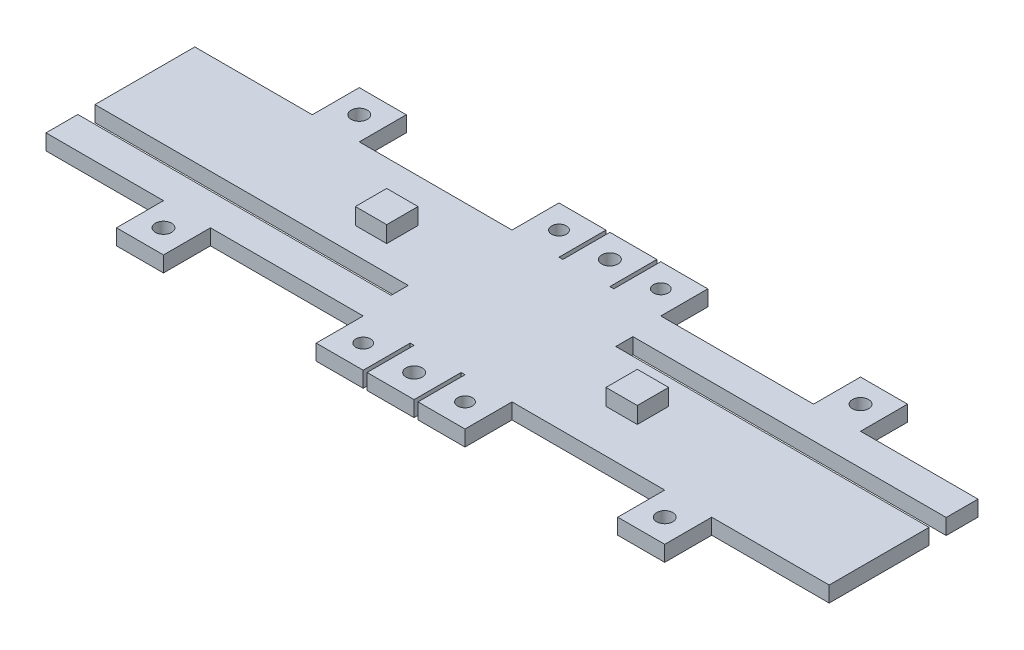
SolidWorks part; units mm, degrees
ref_plane "Front Plane" through (0, 0, 0) normal (0, 0, 1) x (1, 0, 0)
ref_plane "Top Plane" through (0, 0, 0) normal (0, 1, 0) x (1, 0, 0)
ref_plane "Right Plane" through (0, 0, 0) normal (1, 0, 0) x (0, 0, -1)
sketch "Sketch1" plane through (0, 0, 0) normal (0, 1, 0) x (1, 0, 0)
  line L1 (0, 0) -> (160, 0)
  line L2 (0, 0) -> (0, -30.4)
  line L3 (0, -30.4) -> (160, -30.4)
  line L4 (160, 0) -> (160, -30.4)
  dimension "D1" = 30.4
  dimension "D2" = 160
extrude "Boss-Extrude1" add sketch "Sketch1" along normal blind 3.2
sketch "Sketch2" plane through (0, 3.2, 0) normal (0, 1, 0) x (1, 0, 0)
  line L0 (0, -30.4) -> (160, -30.4) construction
  line L1 (24, -30.4) -> (33.6, -30.4)
  line L2 (24, -30.4) -> (24, -40)
  line L3 (24, -40) -> (33.6, -40)
  line L4 (33.6, -30.4) -> (33.6, -40)
  line L5 (75.2, -30.4) -> (75.2, -40)
  line L6 (75.2, -40) -> (84.8, -40)
  line L7 (75.2, -30.4) -> (84.8, -30.4)
  line L8 (84.8, -30.4) -> (84.8, -40)
  line L9 (126.4, -30.4) -> (126.4, -40)
  line L10 (126.4, -40) -> (136, -40)
  line L11 (126.4, -30.4) -> (136, -30.4)
  line L12 (136, -30.4) -> (136, -40)
  line L13 (75.2, 9.6) -> (75.2, 0)
  line L14 (75.2, 0) -> (84.8, 0)
  line L15 (75.2, 9.6) -> (84.8, 9.6)
  line L16 (84.8, 9.6) -> (84.8, 0)
  line L17 (126.4, 9.6) -> (126.4, 0)
  line L18 (126.4, 0) -> (136, 0)
  line L19 (126.4, 9.6) -> (136, 9.6)
  line L20 (136, 9.6) -> (136, 0)
  line L21 (24, 9.6) -> (24, 0)
  line L22 (24, 0) -> (33.6, 0)
  line L23 (24, 9.6) -> (33.6, 9.6)
  line L24 (33.6, 9.6) -> (33.6, 0)
  circle A0 centre (28.8, -35.2) radius 1.65
  circle A1 centre (80, -35.2) radius 1.65
  circle A2 centre (131.2, -35.2) radius 1.65
  circle A3 centre (80, 4.8) radius 1.65
  circle A4 centre (131.2, 4.8) radius 1.65
  circle A5 centre (28.8, 4.8) radius 1.65
  dimension "D5" = 3.3
  dimension "D1" = 9.6
  dimension "D2" = 9.6
  dimension "D3" = 24
  dimension "D6" = 3
  dimension "D4" = 2
extrude "Boss-Extrude2" add sketch "Sketch2" against normal blind 3.2
sketch "Sketch3" plane through (0, 3.2, 0) normal (0, 1, 0) x (1, 0, 0)
  line L0 (0, 0) -> (0, -30.4) construction
  line L1 (0, -20.4) -> (64, -20.4)
  line L2 (0, -20.4) -> (0, -23.9)
  line L3 (0, -23.9) -> (64, -23.9)
  line L4 (64, -20.4) -> (64, -23.9)
  line L5 (160, -30.4) -> (160, 0) construction
  line L6 (160, -6.5) -> (96, -6.5)
  line L7 (160, -6.5) -> (160, -10)
  line L8 (160, -10) -> (96, -10)
  line L9 (96, -6.5) -> (96, -10)
  dimension "D1" = 10.4
  dimension "D2" = 3.5
  dimension "D3" = 3.5
  dimension "D4" = 64
  dimension "D5" = 64
  dimension "D6" = 6.5
extrude "Cut-Extrude1" cut sketch "Sketch3" against normal through all
sketch "Sketch4" plane through (0, 3.2, 0) normal (0, 1, 0) x (1, 0, 0)
  line L0 (33.6, -30.4) -> (75.2, -30.4) construction
  line L1 (64.8, -30.4) -> (74.4, -30.4)
  line L2 (64.8, -30.4) -> (64.8, -40)
  line L3 (64.8, -40) -> (74.4, -40)
  line L4 (74.4, -30.4) -> (74.4, -40)
  line L5 (84.8, -30.4) -> (126.4, -30.4) construction
  line L6 (85.6, -30.4) -> (95.2, -30.4)
  line L7 (85.6, -30.4) -> (85.6, -40)
  line L8 (85.6, -40) -> (95.2, -40)
  line L9 (95.2, -30.4) -> (95.2, -40)
  line L10 (160, -15.2) -> (144.3037, -15.2) construction
  line L11 (160, -30.4) -> (160, -10) construction
  line L12 (85.6, 9.6) -> (95.2, 9.6)
  line L13 (95.2, 0) -> (95.2, 9.6)
  line L14 (85.6, 0) -> (95.2, 0)
  line L15 (85.6, 0) -> (85.6, 9.6)
  line L16 (64.8, 0) -> (74.4, 0)
  line L17 (74.4, 0) -> (74.4, 9.6)
  line L18 (64.8, 9.6) -> (74.4, 9.6)
  line L19 (64.8, 0) -> (64.8, 9.6)
  circle A0 centre (69.6, -35.2) radius 1.5
  circle A1 centre (90.4, -35.2) radius 1.5
  circle A2 centre (90.4, 4.8) radius 1.5
  circle A3 centre (69.6, 4.8) radius 1.5
  dimension "D1" = 9.6
  dimension "D2" = 9.6
  dimension "D8" = 3
  dimension "D9" = 3
  dimension "D3" = 9.6
  dimension "D4" = 9.6
  dimension "D5" = 0.8
  dimension "D6" = 0.8
  dimension "D7" = 15.2
  dimension "D10" = 4.8
  dimension "D11" = 4.8
extrude "Boss-Extrude3" add sketch "Sketch4" against normal blind 3.2
sketch "Sketch5" plane through (0, 3.2, 0) normal (0, 1, 0) x (1, 0, 0)
  line L0 (95.2, -30.4) -> (126.4, -30.4) construction
  line L1 (54.4, -8.8) -> (48, -8.8)
  line L2 (54.4, -8.8) -> (54.4, -15.2)
  line L3 (54.4, -15.2) -> (48, -15.2)
  line L4 (48, -8.8) -> (48, -15.2)
  line L5 (112, -21.6) -> (105.6, -21.6)
  line L6 (112, -21.6) -> (112, -15.2)
  line L7 (112, -15.2) -> (105.6, -15.2)
  line L8 (105.6, -21.6) -> (105.6, -15.2)
  line L9 (64.8, 0) -> (33.6, 0) construction
  line L10 (160, -30.4) -> (160, -10) construction
  line L11 (0, 0) -> (0, -20.4) construction
  dimension "D1" = 6.4
  dimension "D2" = 6.4
  dimension "D3" = 6.4
  dimension "D5" = 8.8
  dimension "D6" = 8.8
  dimension "D7" = 48
  dimension "D8" = 48
extrude "Boss-Extrude4" add sketch "Sketch5" along normal blind 3.36
equation "\"滑动-垂直孔\" = 0.6"
equation "\"滑动-水平孔\" = 0.3"
equation "\"松动-垂直孔\" = 0.3"
equation "\"松动-水平孔\" = 0.1"
equation "\"正常-垂直孔\" = 0.15"
equation "\"正常-水平孔\" = 0"
equation "\"紧缩-垂直孔\" = 0"
equation "\"紧缩-水平孔\" = -0.1"
equation "\"喷嘴宽度\" = \"_喷嘴物理宽度\" * \"_喷嘴宽度系数\""
equation "\"喷嘴厚度\" = \"_物理厚度\" * \"_物理厚度系数\""
equation "\"D1@Sketch1\"=\"喷嘴宽度\"*4*2 + \"喷嘴宽度\"*30"
equation "\"D2@Sketch1\"=\"喷嘴宽度\"*200"
equation "\"喷嘴物理宽度\"= 0.8"
equation "\"喷嘴宽度系数\"= 1"
equation "\"物理厚度\"= 0.4"
equation "\"物理厚度系数\"= 2"
equation "\"D1@Boss-Extrude1\"=\"喷嘴厚度\"*4"
equation "\"D1@Sketch2\"=\"喷嘴宽度\"*12"
equation "\"D2@Sketch2\"=\"D1@Sketch2\""
equation "\"D3@Sketch2\"=\"喷嘴宽度\"*30"
equation "\"D5@Sketch2\"=\"松动-垂直孔\"+3"
equation "\"D1@Boss-Extrude2\"=\"喷嘴厚度\"*4"
equation "\"D1@Sketch3\"=\"喷嘴宽度\"*13"
equation "\"D2@Sketch3\"=\"喷嘴宽度\"*4 + \"滑动-水平孔\""
equation "\"D3@Sketch3\"=\"D2@Sketch3\""
equation "\"D4@Sketch3\"=\"喷嘴宽度\"*80"
equation "\"D5@Sketch3\"=\"D4@Sketch3\""
equation "\"D6@Sketch3\"=(\"D1@Sketch1\"-\"D1@Sketch3\"-\"D3@Sketch3\"-\"D3@Sketch3\")/2"
equation "\"D1@Sketch4\"=\"D1@Sketch2\""
equation "\"D2@Sketch4\"=\"D2@Sketch2\""
equation "\"D3@Sketch4\"=\"D1@Sketch4\""
equation "\"D4@Sketch4\"=\"D2@Sketch4\""
equation "\"D7@Sketch4\"=\"D1@Sketch1\"/2"
equation "\"D1@Boss-Extrude3\"=\"喷嘴厚度\"*4"
equation "\"D8@Sketch4\"=\"紧缩-垂直孔\"+3"
equation "\"D9@Sketch4\"=\"D8@Sketch4\""
equation "\"D6@Sketch4\"=\"喷嘴宽度\"*1"
equation "\"D5@Sketch4\"=\"D6@Sketch4\""
equation "\"D10@Sketch4\"=\"D1@Sketch4\"/2"
equation "\"D11@Sketch4\"=\"D3@Sketch4\"/2"
equation "\"D1@Sketch5\"=\"喷嘴宽度\"*8"
equation "\"D2@Sketch5\"=\"D1@Sketch5\""
equation "\"D3@Sketch5\"=\"D1@Sketch5\""
equation "\"D4@Sketch5\"=\"D1@Sketch5\""
equation "\"D5@Sketch5\"=\"喷嘴宽度\"*11"
equation "\"D6@Sketch5\"=\"D5@Sketch5\""
equation "\"D7@Sketch5\"=\"喷嘴宽度\"*60"
equation "\"D8@Sketch5\"=\"D7@Sketch5\""
equation "\"D1@Boss-Extrude4\"=\"喷嘴厚度\"*4.2"
